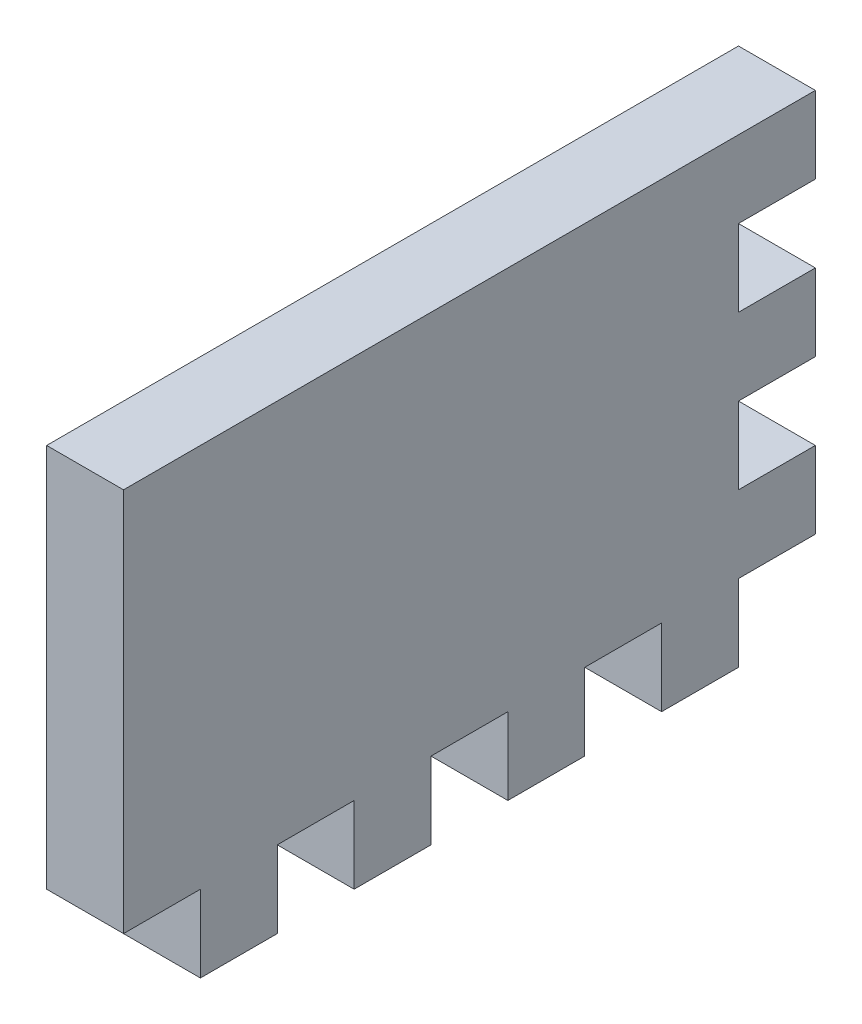
SolidWorks part; units mm, degrees
ref_plane "Front Plane" through (0, 0, 0) normal (0, 0, 1) x (1, 0, 0)
ref_plane "Top Plane" through (0, 0, 0) normal (0, 1, 0) x (1, 0, 0)
ref_plane "Right Plane" through (0, 0, 0) normal (1, 0, 0) x (0, 0, -1)
sketch "Sketch1" plane through (0, 0, 0) normal (1, 0, 0) x (0, 0, -1)
  line L0 (0, 0) -> (12.7, 0)
  line L1 (12.7, 0) -> (12.7, -12.7)
  line L2 (12.7, -12.7) -> (25.4, -12.7)
  line L3 (25.4, -12.7) -> (25.4, 0)
  line L4 (25.4, 0) -> (38.1, 0)
  line L5 (38.1, 0) -> (38.1, -12.7)
  line L6 (38.1, -12.7) -> (50.8, -12.7)
  line L7 (50.8, -12.7) -> (50.8, 0)
  line L8 (50.8, 0) -> (63.5, 0)
  line L9 (63.5, 0) -> (63.5, -12.7)
  line L10 (63.5, -12.7) -> (76.2, -12.7)
  line L11 (76.2, -12.7) -> (76.2, 0)
  line L12 (76.2, 0) -> (88.9, 0)
  line L13 (88.9, 0) -> (88.9, -12.7)
  line L14 (88.9, -12.7) -> (101.6, -12.7)
  line L15 (101.6, -12.7) -> (101.6, 0)
  line L16 (0, 0) -> (0, 63.5)
  line L17 (0, 63.5) -> (101.6, 63.5)
  line L19 (101.6, 0) -> (114.3, 0)
  line L20 (114.3, 0) -> (114.3, 12.7)
  line L21 (114.3, 12.7) -> (101.6, 12.7)
  line L22 (101.6, 12.7) -> (101.6, 25.4)
  line L23 (101.6, 25.4) -> (114.3, 25.4)
  line L24 (114.3, 25.4) -> (114.3, 38.1)
  line L25 (114.3, 38.1) -> (101.6, 38.1)
  line L26 (101.6, 38.1) -> (101.6, 50.8)
  line L27 (101.6, 50.8) -> (114.3, 50.8)
  line L28 (114.3, 50.8) -> (114.3, 63.5)
  line L29 (114.3, 63.5) -> (101.6, 63.5)
  point P18 (107.95, 12.7)
  point P24 (0, 0)
  dimension "D1" = 12.7
  dimension "D2" = 4
  dimension "D3" = 3
extrude "Boss-Extrude1" add sketch "Sketch1" along normal blind 12.7
